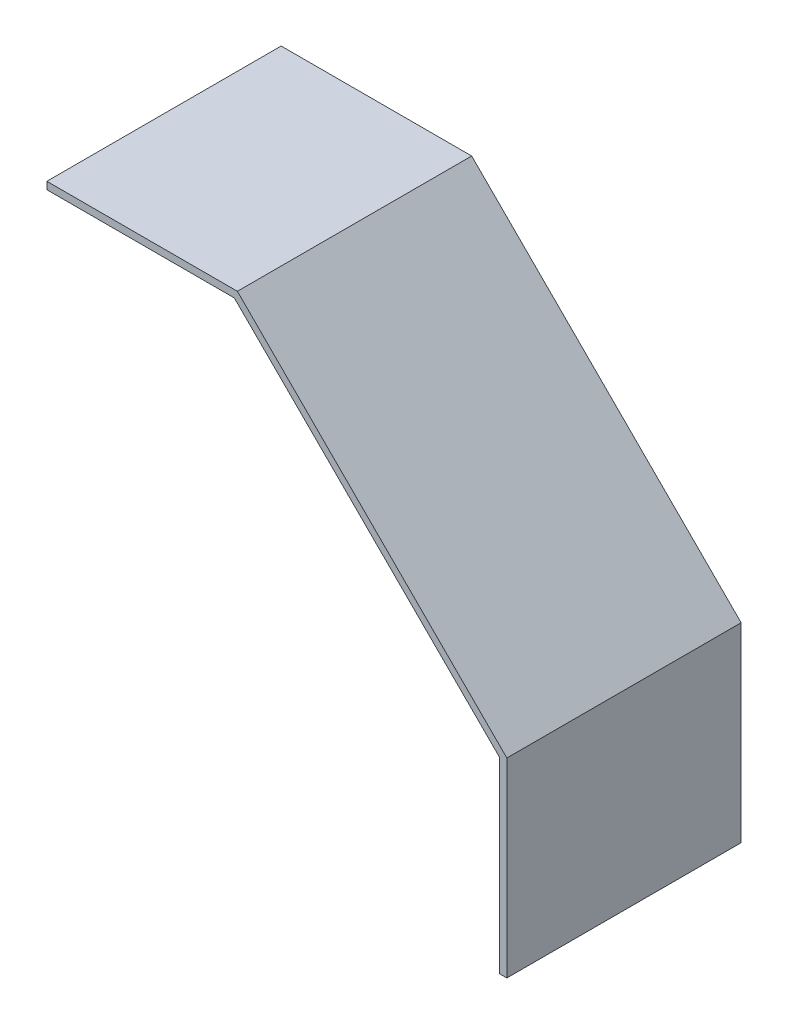
SolidWorks part; units mm, degrees
ref_plane "Front Plane" through (0, 0, 0) normal (0, 0, 1) x (1, 0, 0)
ref_plane "Top Plane" through (0, 0, 0) normal (0, 1, 0) x (1, 0, 0)
ref_plane "Right Plane" through (0, 0, 0) normal (1, 0, 0) x (0, 0, -1)
sketch "Sketch1" plane through (0, 0, 0) normal (0, 0, 1) x (1, 0, 0)
  line L0 (398.9312, 165.2427) -> (398.9312, 0) construction
  line L1 (165.2427, 398.9312) -> (398.9312, 165.2427) construction
  line L2 (0, 398.9312) -> (165.2427, 398.9312) construction
  line L3 (398.9312, 165.2427) -> (398.9312, 0)
  line L4 (165.2427, 398.9312) -> (398.9312, 165.2427)
  line L5 (0, 398.9312) -> (165.2427, 398.9312)
  line L6 (0, 392.5812) -> (162.6124, 392.5812)
  line L7 (162.6124, 392.5812) -> (392.5812, 162.6124)
  line L8 (392.5812, 162.6124) -> (392.5812, 0)
  line L9 (0, 398.9312) -> (0, 392.5812)
  line L10 (398.9312, 0) -> (392.5812, 0)
  dimension "D1" = 6.35
extrude "Boss-Extrude1" add sketch "Sketch1" along normal blind 203.2
